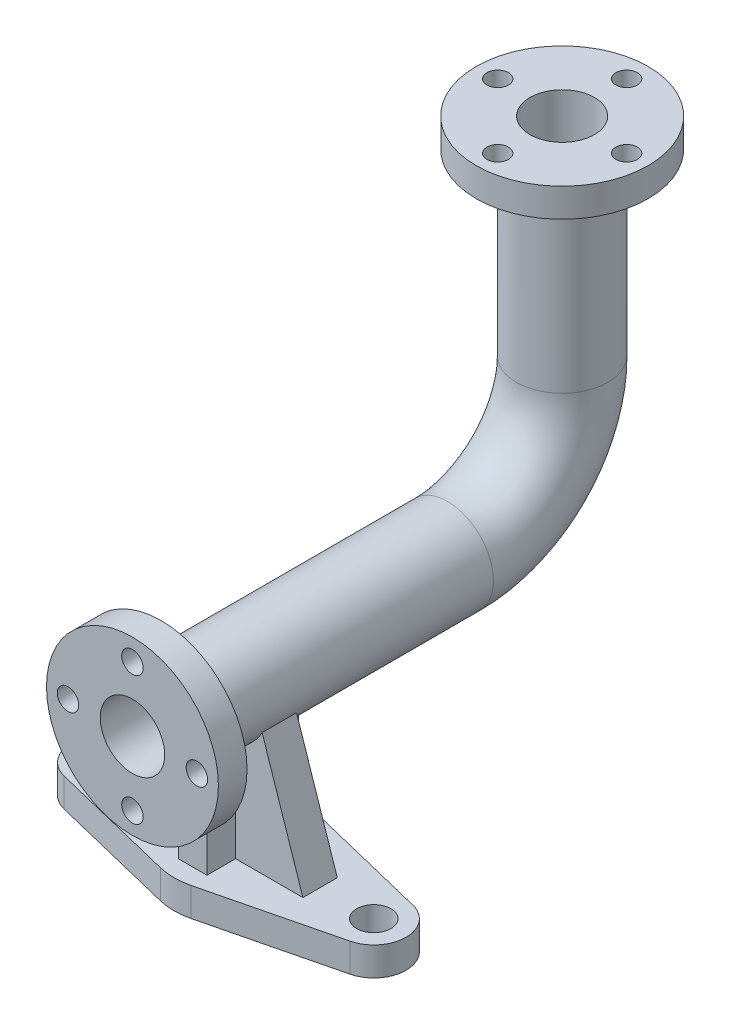
SolidWorks part; units mm, degrees
ref_plane "Front Plane" through (0, 0, 0) normal (0, 0, 1) x (1, 0, 0)
ref_plane "Top Plane" through (0, 0, 0) normal (0, 1, 0) x (1, 0, 0)
ref_plane "Right Plane" through (0, 0, 0) normal (1, 0, 0) x (0, 0, -1)
sketch "Sketch1" plane through (0, 0, 0) normal (0, 0, 1) x (1, 0, 0)
  circle A0 centre (0, 0) radius 32
  circle A1 centre (0, 0) radius 22.5
  dimension "D1" = 64
  dimension "D2" = 45
sketch "Sketch2" plane through (0, 0, 0) normal (1, 0, 0) x (0, 0, -1)
  line L0 (0, 0) -> (200, 0)
  line L1 (280, 80) -> (280, 205)
  arc A0 (200, 0) -> (280, 80) centre (200, 80) ccw
  dimension "D3" = 80
  dimension "D1" = 125
  dimension "D2" = 200
sweep "Sweep1" add profiles "Sketch1" path "Sketch2"
sketch "Sketch3" plane through (0, 0, 0) normal (0, 0, 1) x (1, 0, 0)
  circle A0 centre (0, 0) radius 60
  circle A1 centre (0, 0) radius 22.5 construction
  circle A2 centre (0, 0) radius 22.5
  dimension "D1" = 120
extrude "Boss-Extrude1" add sketch "Sketch3" along normal blind 20
sketch "Sketch4" plane through (0, 205, 0) normal (0, 1, 0) x (1, 0, 0)
  circle A0 centre (0, 280) radius 22.5 construction
  circle A1 centre (0, 280) radius 22.5
  circle A2 centre (0, 280) radius 60
  dimension "D1" = 120
extrude "Boss-Extrude2" add sketch "Sketch4" along normal blind 20
sketch "Sketch7" plane through (0, 0, 20) normal (0, 0, 1) x (1, 0, 0)
  point P0 (45, 0)
  dimension "D1" = 45
hole_wizard "Hole1" positions "Sketch7" profile "Sketch6" legacy
sketch "Sketch6" plane through (45, 0, 20) normal (1, 0, 0) x (0, -1, 0)
  line L0 (0, 0) -> (0, 20)
  line L1 (0, 20) -> (7.5, 20)
  line L2 (7.5, 20) -> (7.5, 0)
  line L3 (7.5, 0) -> (0, 0)
  line L4 (0, 110) -> (0, -10) construction
  dimension "Diameter" = 15
  dimension "Depth" = 20
pattern_circular "CirPattern1" count 4 over 360 about axis through (0, 0, 0) along (0, 0, 1) of "Hole1"
sketch "Sketch11" plane through (0, 225, 0) normal (0, 1, 0) x (1, 0, 0)
  point P0 (0, 235)
  dimension "D1" = 45
hole_wizard "Hole2" positions "Sketch11" profile "Sketch10" legacy
sketch "Sketch10" plane through (0, 225, -235) normal (1, 0, 0) x (0, 0, 1)
  line L0 (0, 0) -> (0, 20)
  line L1 (0, 20) -> (7.5, 20)
  line L2 (7.5, 20) -> (7.5, 0)
  line L3 (7.5, 0) -> (0, 0)
  line L4 (0, 110) -> (0, -10) construction
  dimension "Diameter" = 15
  dimension "Depth" = 20
pattern_circular "CirPattern2" count 4 over 360 about axis through (0, 0, -280) along (0, 1, 0) of "Hole2"
ref_plane "Plane1" through (0, -120, 0) normal (0, 1, 0) x (1, 0, 0)
sketch "Sketch12" plane through (0, -120, 0) normal (0, 1, 0) x (1, 0, 0)
  line L0 (10.7143, 97.7059) -> (99.8571, 75.8529)
  line L1 (-99.8571, 75.8529) -> (-10.7143, 97.7059)
  line L3 (10.7143, 10.2941) -> (99.8571, 32.1471)
  line L4 (-99.8571, 32.1471) -> (-10.7143, 10.2941)
  arc A0 (-10.7143, 10.2941) -> (10.7143, 10.2941) centre (0, 54) ccw
  arc A1 (99.8571, 32.1471) -> (99.8571, 75.8529) centre (94.5, 54) ccw
  arc A2 (-99.8571, 75.8529) -> (-99.8571, 32.1471) centre (-94.5, 54) ccw
  arc A3 (10.7143, 97.7059) -> (-10.7143, 97.7059) centre (0, 54) ccw
  circle A4 centre (-94.5, 54) radius 12
  circle A5 centre (94.5, 54) radius 12
  dimension "D1" = 45
  dimension "D2" = 90
  dimension "D5" = 24
  dimension "D6" = 24
  dimension "D3" = 94.5
  dimension "D4" = 74
extrude "Boss-Extrude3" add sketch "Sketch12" along normal blind 20 separate body
ref_plane "Plane2" through (0, 0, -54) normal (0, 0, 1) x (1, 0, 0)
sketch "Sketch13" plane through (0, 0, -54) normal (0, 0, 1) x (1, 0, 0)
  circle A0 centre (0, 0) radius 22.5 construction
  circle A1 centre (0, 0) radius 22.5
  circle A2 centre (0, 0) radius 27.25
  dimension "D1" = 54.5
sketch "Sketch14" plane through (0, 0, 20) normal (0, 0, 1) x (1, 0, 0)
  circle A1 centre (0, 0) radius 22.5 construction
  circle A2 centre (0, 0) radius 22.5
sketch "Sketch17" plane through (0, 0, -54) normal (0, 0, 1) x (1, 0, 0)
  line L7 (0, 45) -> (0, -72.6649) construction
  circle A2 centre (0, 0) radius 22.5 construction
  circle A3 centre (0, 0) radius 22.5
sketch "Sketch18" plane through (0, 0, -54) normal (0, 0, 1) x (1, 0, 0)
  line L2 (8.6301, 35.0488) -> (70.8253, -100)
  line L6 (10.7143, -100) -> (99.8571, -100) construction
  line L8 (70.8253, -100) -> (-77.1132, -100)
  line L9 (-99.8571, -100) -> (-10.7143, -100) construction
  line L10 (-77.1132, -100) -> (-4.004, 41.2023)
  circle A4 centre (0, 0) radius 22.5 construction
sketch "Sketch19" plane through (0, 0, -54) normal (0, 0, 1) x (1, 0, 0)
  line L0 (21.3484, 7.1061) -> (57, -100)
  line L1 (10.7143, -100) -> (99.8571, -100) construction
  line L2 (57, -100) -> (-57, -100)
  line L3 (-99.8571, -100) -> (-10.7143, -100) construction
  line L4 (-57, -100) -> (-21.3484, 7.1061)
  circle A0 centre (0, 0) radius 22.5 construction
  arc A1 (-21.3484, 7.1061) -> (21.3484, 7.1061) centre (0, 0) ccw
  dimension "D1" = 114
extrude "Boss-Extrude4" add sketch "Sketch19" along normal mid plane 24 contours L0 L2 L4 A1
sketch "Sketch21" plane through (0, 0, 0) normal (1, 0, 0) x (0, 0, -1)
  line L0 (54, -14.4834) -> (54, -115.5155) construction
  line L14 (22, -25.2006) -> (86, -25.2006)
  line L15 (22, -25.2006) -> (22, -106.484)
  line L16 (22, -106.484) -> (86, -106.484)
  line L17 (86, -25.2006) -> (86, -106.484)
  line L18 (42, -14.4834) -> (66, -14.4834) construction
  dimension "D1" = 64
extrude "Boss-Extrude5" add sketch "Sketch21" along normal mid plane 20
